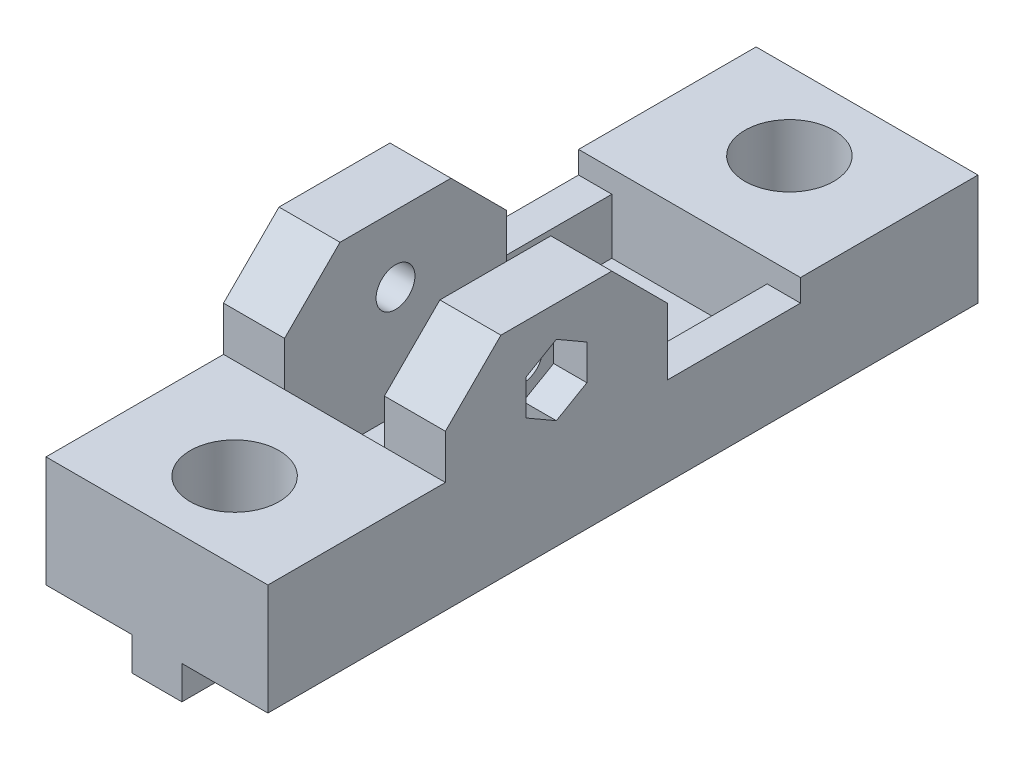
SolidWorks part; units mm, degrees
ref_plane "Front Plane" through (0, 0, 0) normal (0, 0, 1) x (1, 0, 0)
ref_plane "Top Plane" through (0, 0, 0) normal (0, 1, 0) x (1, 0, 0)
ref_plane "Right Plane" through (0, 0, 0) normal (1, 0, 0) x (0, 0, -1)
sketch "Sketch1" plane through (0, 0, 0) normal (0, 1, 0) x (1, 0, 0)
  line L1 (-10, -15) -> (10, -15)
  line L2 (-10, -15) -> (-10, 15)
  line L3 (-10, 15) -> (10, 15)
  line L4 (10, -15) -> (10, 15)
  line L5 (-10, -15) -> (10, 15) construction
  line L6 (-10, 15) -> (10, -15) construction
  point P0 (0, 0)
  dimension "D1" = 20
  dimension "D2" = 30
extrude "Boss-Extrude1" add sketch "Sketch1" along normal blind 3
sketch "Sketch2" plane through (0, 0, 0) normal (0, -1, 0) x (1, 0, 0)
  line L0 (10, -15) -> (-10, -15) construction
  line L1 (-2.25, -15) -> (2.25, -15)
  line L2 (-2.25, -15) -> (-2.25, -3)
  line L3 (-2.25, -3) -> (2.25, -3)
  line L4 (2.25, -15) -> (2.25, -3)
  line L5 (-2.25, -15) -> (2.25, -3) construction
  line L6 (-2.25, -3) -> (2.25, -15) construction
  point P0 (0, -9)
  dimension "D1" = 0
  dimension "D2" = 4.5
  dimension "D3" = 0
  dimension "D4" = 12
extrude "Boss-Extrude2" add sketch "Sketch2" along normal blind 3
sketch "Sketch3" plane through (0, 3, 0) normal (0, 1, 0) x (1, 0, 0)
  line L0 (10, 15) -> (-10, 15) construction
  circle A0 centre (0, 8) radius 4
  circle A1 centre (0, 8) radius 7
  dimension "D1" = 14
  dimension "D2" = 7
  dimension "D3" = 8
extrude "Boss-Extrude3" add sketch "Sketch3" along normal blind 7
sketch "Sketch4" plane through (0, 3, 0) normal (0, 1, 0) x (1, 0, 0)
  circle A1 centre (0, 8) radius 4
  circle A2 centre (0, 8) radius 4
  dimension "D1" = 0
extrude "Boss-Extrude4" add sketch "Sketch4" along normal blind 1
sketch "Sketch5" plane through (0, 3, 0) normal (0, 1, 0) x (1, 0, 0)
  line L0 (-10, -15) -> (10, -15) construction
  circle A0 centre (0, -8.5) radius 3
  point P4 (0, 0)
  point P7 (-0.7919, -3)
  dimension "D1" = 6
  dimension "D2" = 6.5
  dimension "D3" = 0
extrude "Cut-Extrude1" cut sketch "Sketch5" against normal through all both and the other way through all
chamfer "Chamfer1" [suppressed] distance 4 angle 45
sketch "Sketch6" plane through (0, 3, 0) normal (0, 1, 0) x (1, 0, 0)
  line L0 (10, -15) -> (10, 15) construction
  line L1 (-10, 15) -> (10, 15)
  line L2 (-10, 15) -> (-10, -1)
  line L3 (-10, -1) -> (10, -1)
  line L4 (10, 15) -> (10, -1)
  circle A0 centre (0, 8) radius 7 construction
  circle A1 centre (0, 8) radius 7
  circle A3 centre (0, 8) radius 4
  circle A4 centre (0, 8) radius 4
  line M6 (10, 15) -> (0, 15)
  circle M7 centre (0, 8) radius 7
  line M8 (0, 15) -> (-10, 15)
  line M9 (-10, 15) -> (-10, -15)
  line M11 (10, -15) -> (10, 15)
  dimension "D1" = 16
  dimension "D2" = 0
extrude "Boss-Extrude6" add sketch "Sketch6" along normal up to surface (7 mm away) contours A4 M7 | L3 M9 M11 M6 M7 M8 up to face at (0, 10, -1)
ref_plane "Plane1" through (0, 0, -8) normal (0, 0, 1) x (1, 0, 0)
ref_plane "Plane2" through (0, 0, 17) normal (0, 0, 1) x (1, 0, 0)
sketch "Sketch7" plane through (0, 0, 15) normal (0, 0, 1) x (1, 0, 0)
  line L4 (-10, 0) -> (10, 0)
  line L5 (10, 0) -> (10, 3)
  line L6 (10, 3) -> (-10, 3)
  line L7 (-10, 3) -> (-10, 0)
  line L8 (-10, 0) -> (10, 0)
  line L9 (10, 0) -> (10, 3)
  line L10 (10, 3) -> (-10, 3)
  line L11 (-10, 3) -> (-10, 0)
  dimension "D1" = 0
extrude "Boss-Extrude7" add sketch "Sketch7" along normal blind 19
mirror "Mirror3" about plane through (0, 0, 17) normal (0, 0, 1) of "Boss-Extrude6", "Boss-Extrude4", "Boss-Extrude3", "Boss-Extrude2", "Boss-Extrude1"
sketch "Sketch8" plane through (0, 0, 37) normal (0, 0, -1) x (-1, 0, 0)
  line L4 (2.25, 0) -> (-2.25, 0)
  line L5 (-2.25, 0) -> (-2.25, -3)
  line L6 (-2.25, -3) -> (2.25, -3)
  line L7 (2.25, -3) -> (2.25, 0)
  line L8 (2.25, 0) -> (-2.25, 0)
  line L9 (-2.25, 0) -> (-2.25, -3)
  line L10 (-2.25, -3) -> (2.25, -3)
  line L11 (2.25, -3) -> (2.25, 0)
  dimension "D1" = 0
extrude "Boss-Extrude8" add sketch "Sketch8" along normal blind 12
sketch "Sketch10" plane through (0, 3, 0) normal (0, 1, 0) x (1, 0, 0)
  line L0 (-10, -33) -> (10, -33) construction
  line L1 (4.5, -13) -> (-4.5, -13)
  line L2 (4.5, -13) -> (4.5, -33)
  line L3 (4.5, -33) -> (-4.5, -33)
  line L4 (-4.5, -13) -> (-4.5, -33)
  line L5 (4.5, -13) -> (-4.5, -33) construction
  line L6 (4.5, -33) -> (-4.5, -13) construction
  line L8 (-10, -1) -> (-10, -33) construction
  line L9 (-4.5, -13) -> (-10, -13)
  line L10 (-4.5, -13) -> (-4.5, -33)
  line L11 (-4.5, -33) -> (-10, -33)
  line L12 (-10, -13) -> (-10, -33)
  line L14 (4.5, -13) -> (10, -13)
  line L15 (4.5, -13) -> (4.5, -33)
  line L16 (4.5, -33) -> (10, -33)
  line L17 (10, -13) -> (10, -33)
  circle A0 centre (0, -8.5) radius 3 construction
  circle A1 centre (0, -8.5) radius 3
  circle A2 centre (0, -8.5) radius 6
  point P0 (0, -23)
  line M15 (-10, -1) -> (-10, -33)
  line M16 (-10, -33) -> (10, -33)
  line M17 (10, -33) -> (10, -1)
  dimension "D4" = 12
  dimension "D1" = 0
  dimension "D2" = 20
  dimension "D3" = 9
extrude "Boss-Extrude9" add sketch "Sketch10" along normal blind 16 contours L4 L9 M15 M16 | L14 L2 M16 M17
sketch "Sketch11" plane through (-10, 0, 0) normal (-1, 0, 0) x (0, 0, 1)
  line L0 (17, -11) -> (17, 11) construction
  circle A0 centre (23, 13) radius 1.75
  dimension "D3" = 3.5
  dimension "D1" = 6
  dimension "D2" = 10
extrude "Cut-Extrude2" cut sketch "Sketch11" against normal through all both and the other way through all
sketch "Sketch12" plane through (-10, 0, 0) normal (-1, 0, 0) x (0, 0, 1)
  circle A0 centre (23, 13) radius 1.75 construction
  circle A1 centre (23, 13) radius 1.75
  circle A2 centre (23, 13) radius 3
  dimension "D1" = 6
extrude "Cut-Extrude3" cut sketch "Sketch12" against normal blind 3
sketch "Sketch13" plane through (10, 0, 0) normal (1, 0, 0) x (0, 0, -1)
  line L1 (-23, 16.1754) -> (-25.75, 14.5877)
  line L2 (-25.75, 14.5877) -> (-25.75, 11.4123)
  line L3 (-25.75, 11.4123) -> (-23, 9.8246)
  line L4 (-23, 9.8246) -> (-20.25, 11.4123)
  line L5 (-20.25, 11.4123) -> (-20.25, 14.5877)
  line L6 (-20.25, 14.5877) -> (-23, 16.1754)
  circle A0 centre (-23, 13) radius 1.75 construction
  circle A1 centre (-23, 13) radius 1.75
  circle A2 centre (-23, 13) radius 2.75 construction
  dimension "D1" = 5.5
extrude "Cut-Extrude4" cut sketch "Sketch13" against normal blind 3
chamfer "Chamfer2" distance 5 angle 45 4 edges at (7.25, 19, 13) (7.25, 19, 33) (-7.25, 19, 33) (-7.25, 19, 13)
sketch "Sketch14" plane through (0, 4, 0) normal (0, 1, 0) x (1, 0, 0)
  circle A0 centre (0, -42) radius 4 construction
  circle A1 centre (0, 8) radius 4 construction
  circle A2 centre (0, -42) radius 4
  circle A3 centre (0, 8) radius 4
extrude "Cut-Extrude5" cut sketch "Sketch14" against normal blind 1.5
sketch "Sketch15" plane through (0, 3, 0) normal (0, 1, 0) x (1, 0, 0)
  line L1 (-10, -1) -> (-7, -1)
  line L2 (-10, -1) -> (-10, -13)
  line L3 (-10, -13) -> (-7, -13)
  line L4 (-7, -1) -> (-7, -13)
  line L5 (10, -1) -> (7, -1)
  line L6 (10, -1) -> (10, -13)
  line L7 (10, -13) -> (7, -13)
  line L8 (4.5, -33) -> (4.5, -13)
  line L9 (4.5, -13) -> (10, -13)
  line L10 (10, -13) -> (10, -1)
  line L11 (10, -1) -> (-10, -1)
  line L12 (-10, -1) -> (-10, -13)
  line L13 (-10, -13) -> (-4.5, -13)
  line L14 (-4.5, -13) -> (-4.5, -33)
  line L15 (-4.5, -33) -> (4.5, -33)
  line L16 (4.5, -33) -> (4.5, -13)
  line L17 (4.5, -13) -> (10, -13)
  line L18 (10, -13) -> (10, -1)
  line L19 (10, -1) -> (-10, -1)
  line L20 (-10, -1) -> (-10, -13)
  line L21 (-10, -13) -> (-4.5, -13)
  line L22 (-4.5, -13) -> (-4.5, -33)
  line L23 (-4.5, -33) -> (4.5, -33)
  line L24 (7, -1) -> (7, -13)
  line M15 (4.5, -13) -> (10, -13)
  line M16 (10, -13) -> (10, -1)
  line M17 (10, -1) -> (-10, -1)
  line M18 (-10, -1) -> (-10, -13)
  line M19 (-10, -13) -> (-4.5, -13)
  dimension "D2" = 3
  dimension "D3" = 3
  dimension "D1" = 0
extrude "Boss-Extrude10" add sketch "Sketch15" along normal blind 5 contours L4 M17 M18 M19 | L24 M17 M15 M16
